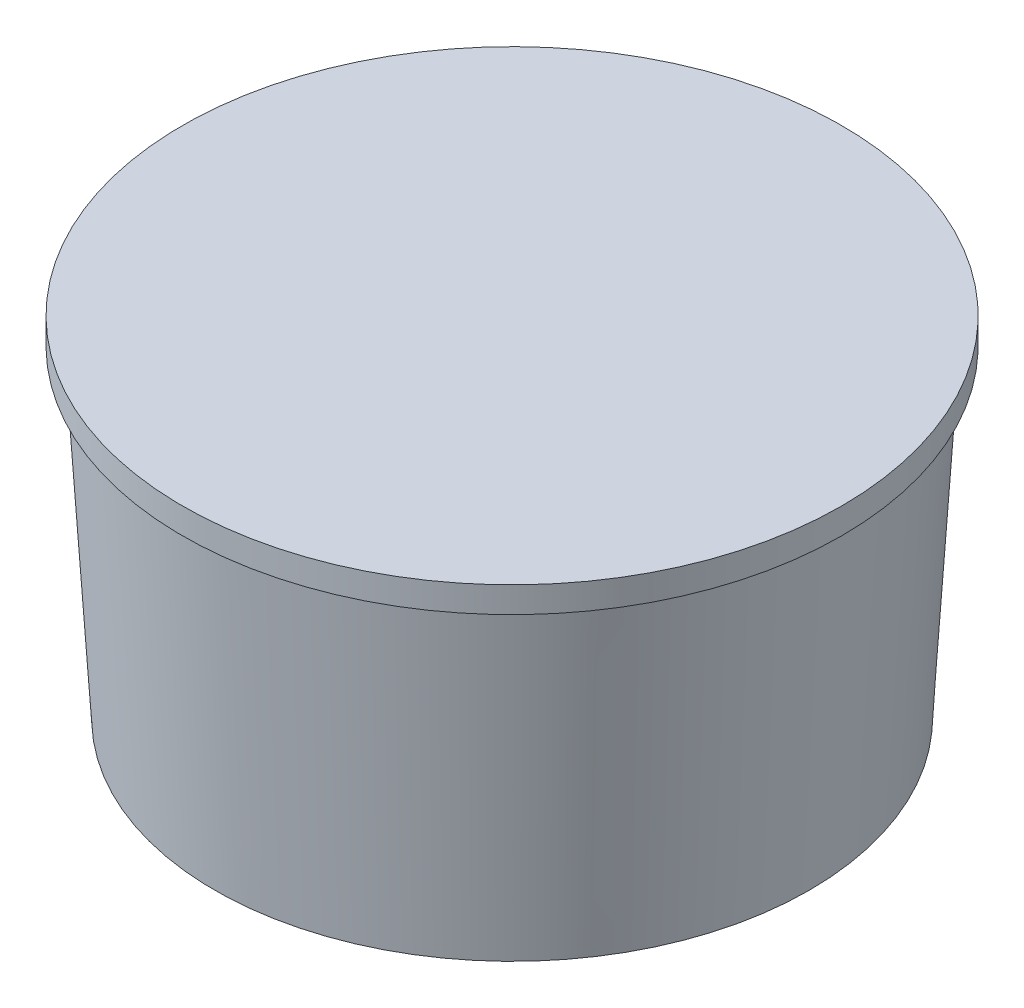
SolidWorks part; units mm, degrees
ref_plane "Front Plane" through (0, 0, 0) normal (0, 0, 1) x (1, 0, 0)
ref_plane "Top Plane" through (0, 0, 0) normal (0, 1, 0) x (1, 0, 0)
ref_plane "Right Plane" through (0, 0, 0) normal (1, 0, 0) x (0, 0, -1)
sketch "Sketch2" plane through (0, 0, 0) normal (0, 0, 1) x (1, 0, 0)
  line L1 (-25.5, 0) -> (-25.5, -2) construction
  line L2 (-25.5, -2) -> (-24.5, -2) construction
  line L3 (-24.5, -2) -> (-23, -27) construction
  line L4 (-23, -27) -> (-22, -27) construction
  line L5 (-22, -27) -> (-22, -2) construction
  line L7 (0, -14.85) -> (0, 14.85) construction
  line L8 (22, -27) -> (22, -2)
  line L9 (23, -27) -> (22, -27)
  line L10 (24.5, -2) -> (23, -27)
  line L11 (25.5, -2) -> (24.5, -2)
  line L12 (25.5, 0) -> (25.5, -2)
  line L13 (0, 0) -> (0, -2) construction
  line L14 (-25.5, 0) -> (0, 0) construction
  line L15 (0, 0) -> (25.5, 0)
  line L16 (-22, -2) -> (0, -2) construction
  line L17 (0, -2) -> (22, -2)
  line L18 (0, -2) -> (0, 0)
  point P17 (0, 0)
  dimension "D1" = 51
  dimension "D2" = 46
  dimension "D3" = 49
  dimension "D4" = 1
  dimension "D5" = 2
  dimension "D6" = 25
revolve "Revolve3" add sketch "Sketch2" angle 360 about L18
fillet "Fillet1" radius 4 1 edges at (22, -2, 0)
